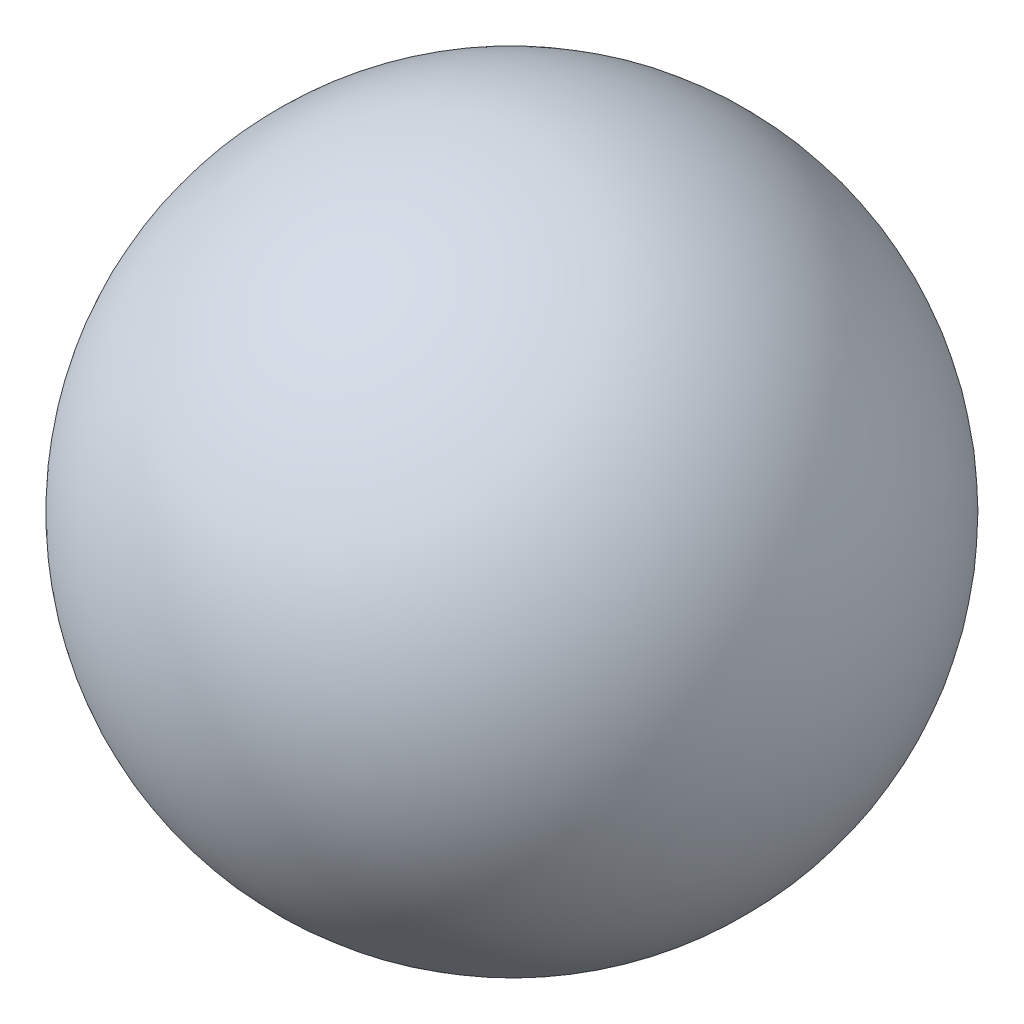
SolidWorks part; units mm, degrees
ref_plane "Front Plane" through (0, 0, 0) normal (0, 0, 1) x (1, 0, 0)
ref_plane "Top Plane" through (0, 0, 0) normal (0, 1, 0) x (1, 0, 0)
ref_plane "Right Plane" through (0, 0, 0) normal (1, 0, 0) x (0, 0, -1)
sketch "Sketch1" plane through (0, 0, 0) normal (0, 1, 0) x (1, 0, 0)
  line L0 (-15.2985, 12.1721) -> (15.2985, -12.1721) construction
  line L1 (15.2985, -12.1721) -> (-15.2985, 12.1721)
  arc A0 (15.2985, -12.1721) -> (-15.2985, 12.1721) centre (0, 0) ccw
  point P4 (12.1721, 15.2985)
  dimension "D1" = 19.55
revolve "Revolve1" add sketch "Sketch1" angle 360 about L0
